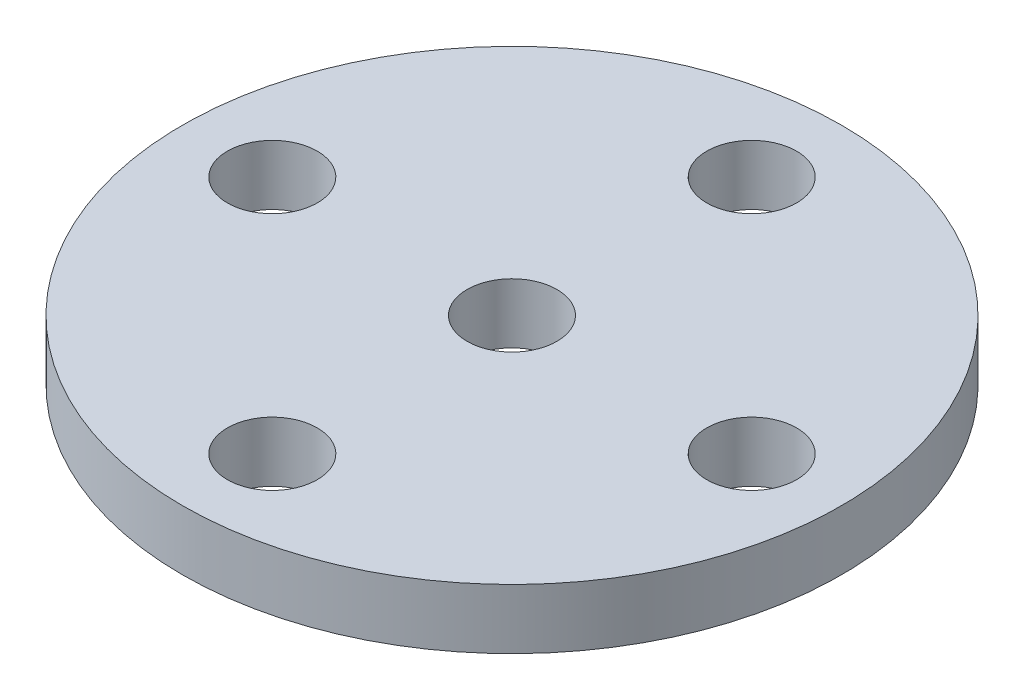
SolidWorks part; units mm, degrees
ref_plane "前视基准面" through (0, 0, 0) normal (0, 0, 1) x (1, 0, 0)
ref_plane "上视基准面" through (0, 0, 0) normal (0, 1, 0) x (1, 0, 0)
ref_plane "右视基准面" through (0, 0, 0) normal (1, 0, 0) x (0, 0, -1)
other "Configuration Table"
sketch "草图1" plane through (0, 0, 0) normal (0, 1, 0) x (1, 0, 0)
  line L0 (0, 0) -> (0, 13.821) construction
  line L1 (0, 0) -> (17.0755, 0) construction
  circle A0 centre (0, 0) radius 11
  circle A1 centre (0, 8) radius 1.5
  circle A2 centre (8, 0) radius 1.5
  circle A3 centre (-8, 0) radius 1.5
  circle A4 centre (0, -8) radius 1.5
  circle A5 centre (0, 0) radius 1.5
  dimension "D1" = 22
  dimension "D2" = 3
  dimension "D3" = 3
  dimension "D4" = 16
  dimension "D5" = 16
  dimension "D6" = 3
extrude "凸台-拉伸1" add sketch "草图1" along normal blind 2
